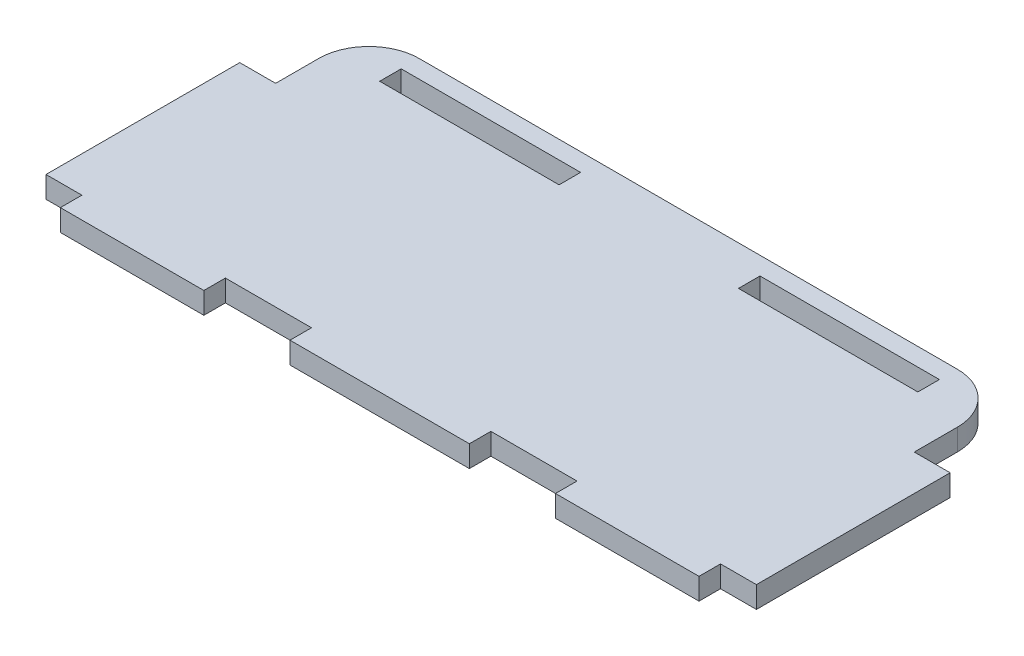
SolidWorks part; units mm, degrees
material "PVC rigido"
ref_plane "Piano frontale" through (0, 0, 0) normal (0, 0, 1) x (1, 0, 0)
ref_plane "Piano superiore" through (0, 0, 0) normal (0, 1, 0) x (1, 0, 0)
ref_plane "Piano destro" through (0, 0, 0) normal (1, 0, 0) x (0, 0, -1)
sketch "Schizzo1" plane through (0, 0, 0) normal (0, 0, 1) x (1, 0, 0)
  line L1 (-44.5, -24) -> (44.5, -24)
  line L2 (-44.5, -24) -> (-44.5, -21)
  line L3 (-44.5, -21) -> (44.5, -21)
  line L4 (44.5, -24) -> (44.5, -21)
extrude "Estrusione-Estrusione1" add sketch "Schizzo1" along normal up to surface (30 mm away) and the other way up to surface (3 mm away)
sketch "Schizzo2" plane through (0, -21, 0) normal (0, 1, 0) x (1, 0, 0)
  line L0 (-44.5, -30) -> (44.5, -30) construction
  line L1 (24.5, -30) -> (12.5, -30)
  line L2 (24.5, -30) -> (24.5, -27)
  line L3 (24.5, -27) -> (12.5, -27)
  line L4 (12.5, -30) -> (12.5, -27)
  line L5 (24.5, -30) -> (24.5, -27) construction
  line L6 (-12.5, -30) -> (-24.5, -30)
  line L7 (-12.5, -30) -> (-12.5, -27)
  line L8 (-12.5, -27) -> (-24.5, -27)
  line L9 (-24.5, -30) -> (-24.5, -27)
  line L10 (12.5, -30) -> (12.5, -27) construction
  line L11 (-24.5, -30) -> (-24.5, -27) construction
extrude "Taglio-Estrusione1" cut sketch "Schizzo2" against normal blind 10
ref_plane "Piano1" through (0, 0, 0) normal (1, 0, 0) x (0, 0, -1)
sketch "Schizzo3" plane through (44.5, 0, 0) normal (1, 0, 0) x (0, 0, -1)
  line L0 (-30, -24) -> (3, -24) construction
  line L1 (0, -21) -> (-27, -21)
  line L2 (0, -21) -> (0, -24)
  line L3 (0, -24) -> (-27, -24)
  line L4 (-27, -21) -> (-27, -24)
  line L5 (-27, -21) -> (-27, -24) construction
extrude "Estrusione-Estrusione2" add sketch "Schizzo3" along normal blind 5
mirror "Specchia1" about plane through (0, 0, 0) normal (1, 0, 0) of "Estrusione-Estrusione2"
sketch "Schizzo4" plane through (0, 0, -3) normal (0, 0, -1) x (-1, 0, 0)
  line L1 (44.5, -21) -> (-44.5, -21)
  line L2 (44.5, -21) -> (44.5, -24)
  line L3 (44.5, -24) -> (-44.5, -24)
  line L4 (-44.5, -21) -> (-44.5, -24)
extrude "Estrusione-Estrusione3" add sketch "Schizzo4" along normal blind 10
sketch "Schizzo5" plane through (0, -21, 0) normal (0, 1, 0) x (1, 0, 0)
  line L0 (-12.5, 9) -> (12.5, 9) construction
  line L1 (-37.5, 10.5) -> (-12.5, 10.5)
  line L2 (-37.5, 10.5) -> (-37.5, 7.5)
  line L3 (-37.5, 7.5) -> (-12.5, 7.5)
  line L4 (-12.5, 10.5) -> (-12.5, 7.5)
  line L5 (12.5, 10.5) -> (37.5, 10.5)
  line L6 (12.5, 10.5) -> (12.5, 7.5)
  line L7 (12.5, 7.5) -> (37.5, 7.5)
  line L8 (37.5, 10.5) -> (37.5, 7.5)
  line L9 (0, 9) -> (0, 13) construction
  line L10 (-44.5, 13) -> (44.5, 13) construction
  line L11 (-37.5, 9) -> (-44.5, 9) construction
  line L12 (-44.5, 0) -> (-44.5, 13) construction
  line L13 (37.5, 9) -> (44.5, 9) construction
  line L14 (44.5, 0) -> (44.5, 13) construction
  dimension "D1" = 3
  dimension "D2" = 4
  dimension "D3" = 25
  dimension "D4" = 25
extrude "Taglio-Estrusione2" cut sketch "Schizzo5" against normal blind 8
fillet "Raccordo1" radius 7 2 edges at (-44.5, -22.5, -13) (44.5, -22.5, -13)
